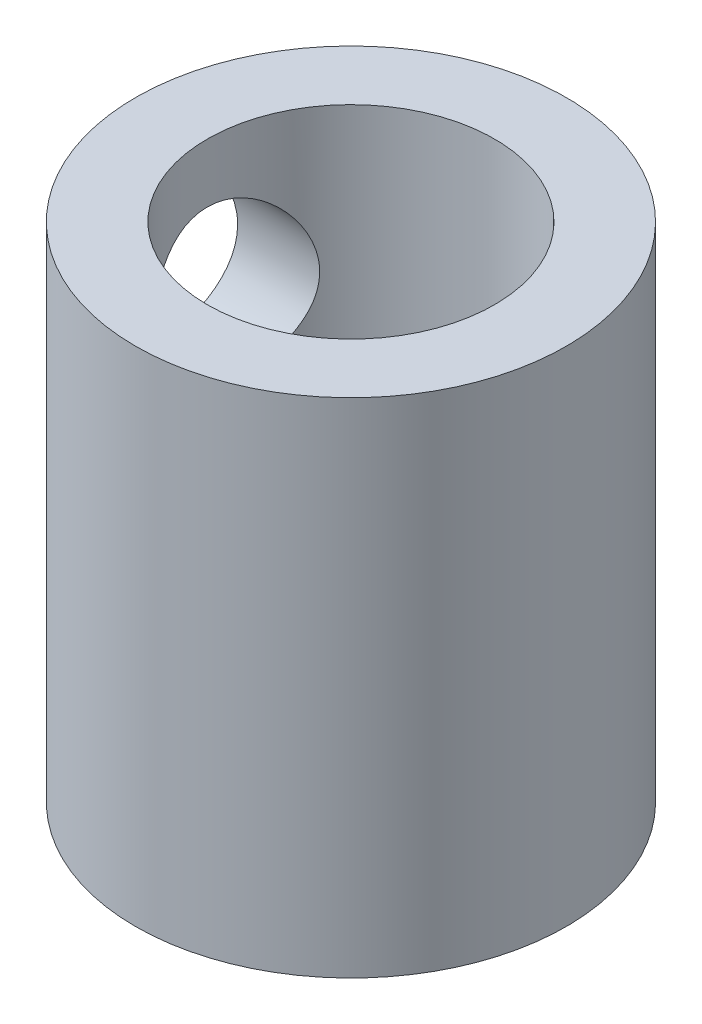
SolidWorks part; units mm, degrees
ref_plane "Front Plane" through (0, 0, 0) normal (0, 0, 1) x (1, 0, 0)
ref_plane "Top Plane" through (0, 0, 0) normal (0, 1, 0) x (1, 0, 0)
ref_plane "Right Plane" through (0, 0, 0) normal (1, 0, 0) x (0, 0, -1)
sketch "Sketch1" plane through (0, 0, 0) normal (0, 1, 0) x (1, 0, 0)
  circle A0 centre (0, 0) radius 10
  circle A1 centre (0, 0) radius 15
  dimension "D1" = 20
  dimension "D2" = 5
extrude "Boss-Extrude1" add sketch "Sketch1" along normal blind 35
sketch "Sketch3" plane through (0, 0, 0) normal (1, 0, 0) x (0, 0, -1)
  circle A0 centre (0, 25) radius 5.9
  dimension "D2" = 11.8
  dimension "D1" = 25
extrude "Cut-Extrude1" cut sketch "Sketch3" against normal up to next
